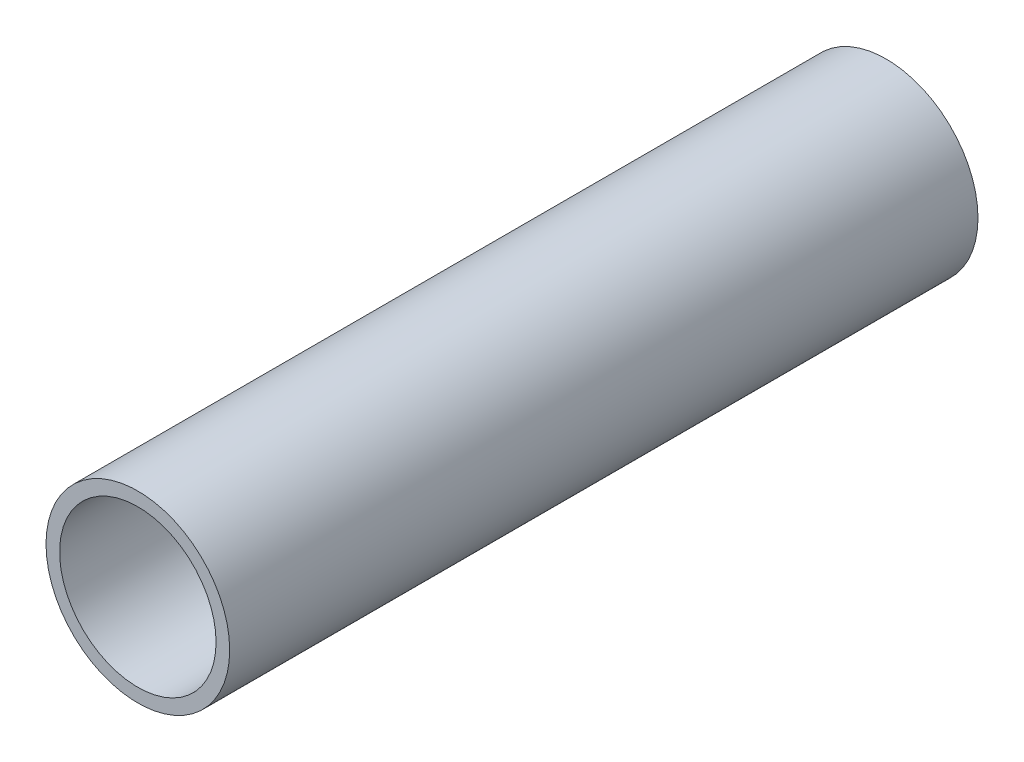
SolidWorks part; units mm, degrees
ref_plane "前视基准面" through (0, 0, 0) normal (0, 0, 1) x (1, 0, 0)
ref_plane "上视基准面" through (0, 0, 0) normal (0, 1, 0) x (1, 0, 0)
ref_plane "右视基准面" through (0, 0, 0) normal (1, 0, 0) x (0, 0, -1)
other "Configuration Table"
sketch "AICAD_SKETCH_F001" plane through (0, 0, 0) normal (0, 0, 1) x (1, 0, 0)
  circle A0 centre (0, 0) radius 13.5
  point P0 (0, 0)
  dimension "D1" = 13.5
extrude "AICAD_F001_BASE_EXTRUDE" add sketch "AICAD_SKETCH_F001" along normal blind 110
sketch "AICAD_SKETCH_F002" plane through (0, 0, 110) normal (0, 0, 1) x (1, 0, 0)
  circle A0 centre (0, 0) radius 11.5
  point P0 (0, 0)
  dimension "D1" = 11.5
extrude "AICAD_F002_CUT_EXTRUDE" cut sketch "AICAD_SKETCH_F002" against normal through all
